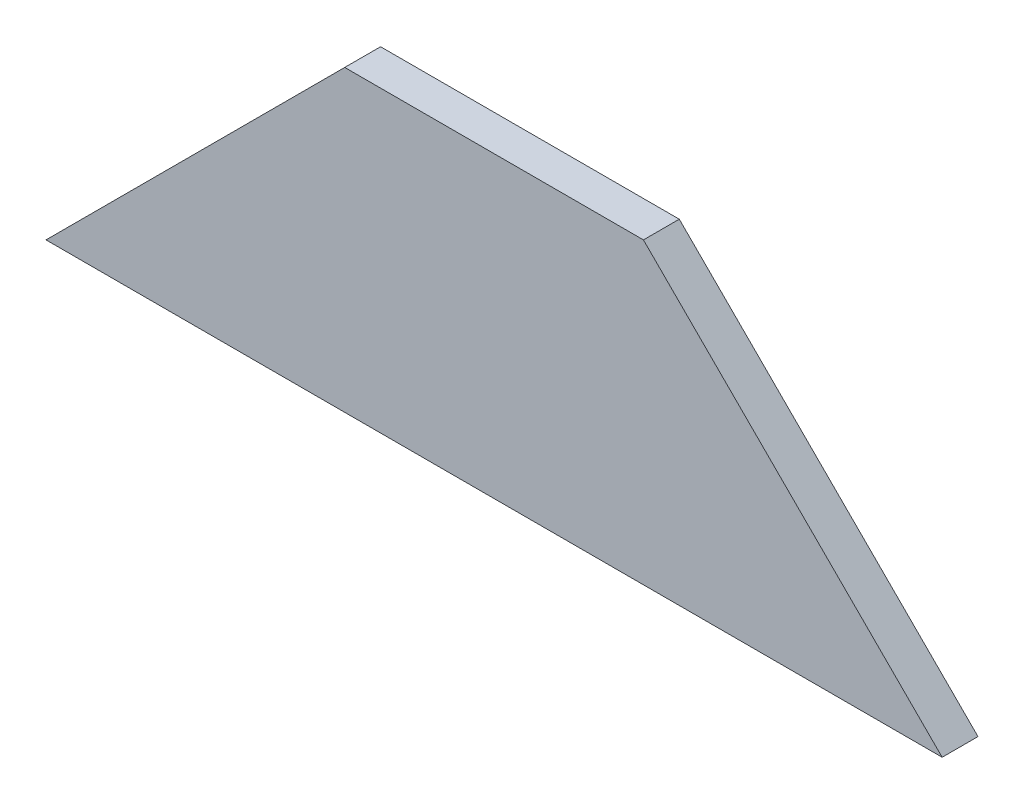
SolidWorks part; units mm, degrees
ref_plane "Front Plane" through (0, 0, 0) normal (0, 0, 1) x (1, 0, 0)
ref_plane "Top Plane" through (0, 0, 0) normal (0, 1, 0) x (1, 0, 0)
ref_plane "Right Plane" through (0, 0, 0) normal (1, 0, 0) x (0, 0, -1)
sketch "Sketch1" plane through (0, 0, 0) normal (0, 0, 1) x (1, 0, 0)
  line L0 (0, 0) -> (-50, 50)
  line L1 (-100, 50) -> (-50, 50)
  line L3 (-150, 0) -> (0, 0)
  line L5 (-150, 0) -> (-100, 50)
  dimension "D1" = 45
  dimension "D2" = 50
  dimension "D3" = 150
extrude "Extrude1" add sketch "Sketch1" along normal blind 6
